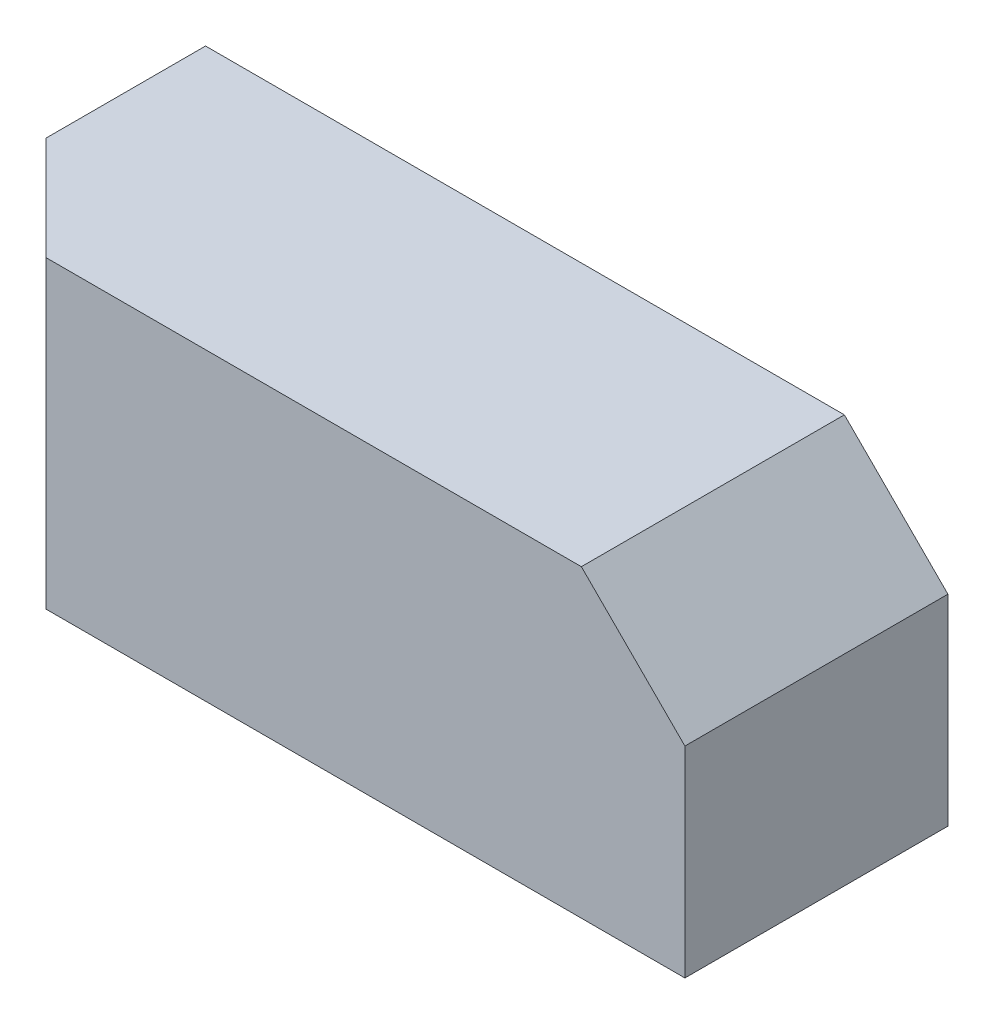
SolidWorks part; units mm, degrees
ref_plane "Front Plane" through (0, 0, 0) normal (0, 0, 1) x (1, 0, 0)
ref_plane "Top Plane" through (0, 0, 0) normal (0, 1, 0) x (1, 0, 0)
ref_plane "Right Plane" through (0, 0, 0) normal (1, 0, 0) x (0, 0, -1)
sketch "Sketch1" plane through (0, 0, 0) normal (0, 0, 1) x (1, 0, 0)
  line L1 (0, 0) -> (71.6952, 0)
  line L2 (0, 0) -> (0, 39.4012)
  line L3 (0, 39.4012) -> (71.6952, 39.4012)
  line L4 (71.6952, 0) -> (71.6952, 39.4012)
extrude "Boss-Extrude1" add sketch "Sketch1" along normal blind 25.4
chamfer "Chamfer1" distance 10 angle 45 6 edges at (71.6952, 39.4012, 12.7) (0, 0, 12.7) (35.8476, 0, 0) (71.6952, 0, 12.7) (35.8476, 0, 25.4) (0, 19.7006, 25.4)
scale "Scale1" scale about centroid uniform scaling yes scale factor 0.5
